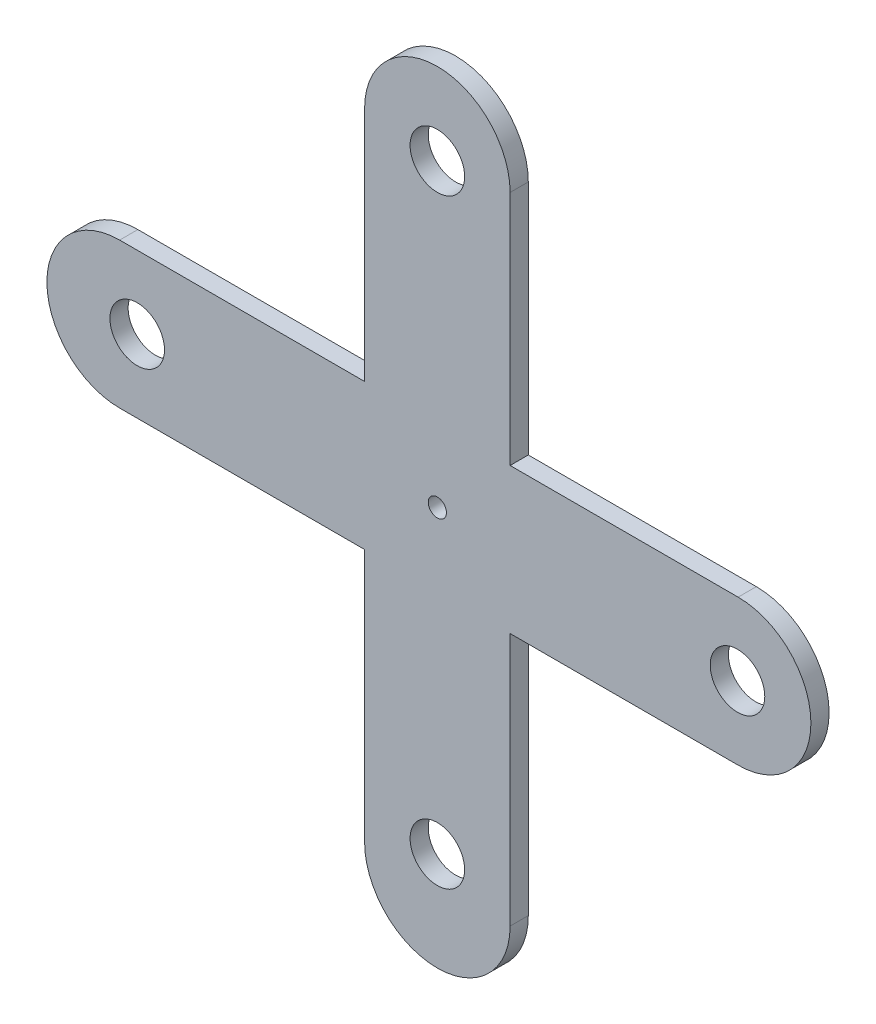
SolidWorks part; units mm, degrees
ref_plane "Plan de face" through (0, 0, 0) normal (0, 0, 1) x (1, 0, 0)
ref_plane "Plan de dessus" through (0, 0, 0) normal (0, 1, 0) x (1, 0, 0)
ref_plane "Plan de droite" through (0, 0, 0) normal (1, 0, 0) x (0, 0, -1)
sketch "Esquisse1" plane through (0, 0, 0) normal (0, 0, 1) x (1, 0, 0)
  line L0 (0, -18.4697) -> (0, 15.5303) construction
  line L1 (-17, -1.4697) -> (17, -1.4697) construction
  line L2 (0, -1.4697) -> (-4, 2.5303) construction
  line L3 (-4, 2.5303) -> (-4, 15.5303)
  line L5 (-17.4645, 2.5303) -> (-4, 2.5303)
  line L6 (4, 2.5303) -> (16.5355, 2.5303)
  line L7 (4, 2.5303) -> (4, 15.5303)
  line L8 (4, -5.4697) -> (4, -19.3986)
  line L9 (4, -5.4697) -> (16.5355, -5.4697)
  line L10 (-4, -5.4697) -> (-17.4645, -5.4697)
  line L11 (-4, -5.4697) -> (-4, -19.3986)
  arc A4 (4, 15.5303) -> (-4, 15.5303) centre (0, 15.5303) ccw
  arc A5 (16.5355, 2.5303) -> (16.5355, -5.4697) centre (16.5355, -1.4697) cw
  arc A6 (4, -19.3986) -> (-4, -19.3986) centre (0, -19.3986) cw
  arc A7 (-17.4645, -5.4697) -> (-17.4645, 2.5303) centre (-17.4645, -1.4697) cw
  point P5 (0, -1.4697)
  point P6 (0, -1.4697)
  dimension "D1" = 8
  dimension "D4" = 8
  dimension "D2" = 8
  dimension "D3" = 4
  dimension "D5" = 4
  dimension "D6" = 4
  dimension "D7" = 4
  dimension "D8" = 4
extrude "Boss.-Extru.1" add sketch "Esquisse1" along normal blind 1
sketch "Esquisse2" plane through (0, 0, 1) normal (0, 0, 1) x (1, 0, 0)
  line L0 (-4, -5.4697) -> (4, 2.5303) construction
  line L1 (4, 2.5303) -> (4, -5.4697) construction
  line L2 (0, -17.9697) -> (0, 15.0303) construction
  line L3 (4, -5.4697) -> (16.5355, -5.4697) construction
  line L4 (4, -19.3986) -> (4, -5.4697) construction
  line L5 (4, -5.4697) -> (-4, 2.5303) construction
  circle A4 centre (0, 15.0303) radius 1.5
  circle A5 centre (16.5, -1.4697) radius 1.5
  circle A6 centre (0, -17.9697) radius 1.5
  circle A7 centre (-16.5, -1.4697) radius 1.5
  circle A8 centre (0, -1.4697) radius 0.5
  point P19 (0, -1.4697)
  dimension "D2" = 4
  dimension "D3" = 3
  dimension "D1" = 33
extrude "Enlèv. mat.-Extru.1" cut sketch "Esquisse2" against normal blind 18
